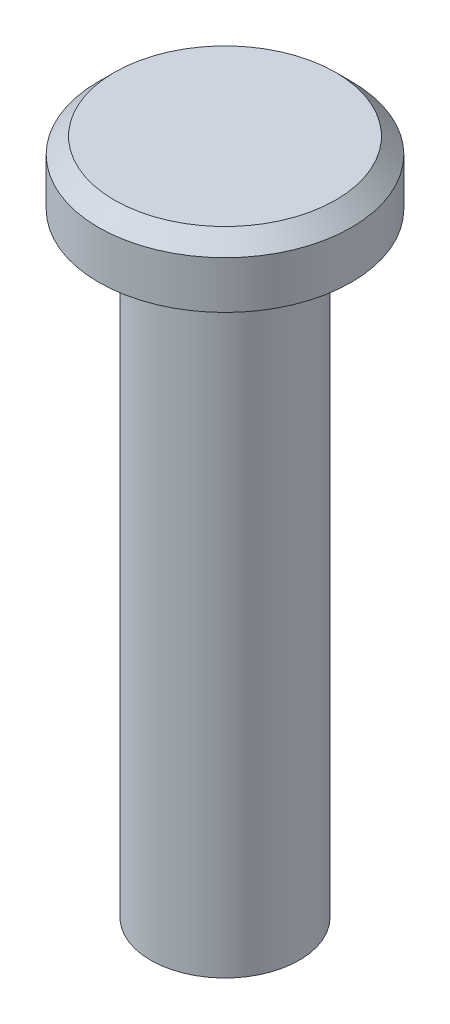
SolidWorks part; units mm, degrees
ref_plane "Front Plane" through (0, 0, 0) normal (0, 0, 1) x (1, 0, 0)
ref_plane "Top Plane" through (0, 0, 0) normal (0, 1, 0) x (1, 0, 0)
ref_plane "Right Plane" through (0, 0, 0) normal (1, 0, 0) x (0, 0, -1)
sketch "Sketch1" plane through (0, 0, 0) normal (0, 1, 0) x (1, 0, 0)
  circle A0 centre (0, 0) radius 2.35
  dimension "D1" = 4.7
extrude "Boss-Extrude1" add sketch "Sketch1" along normal blind 19.4
sketch "Sketch2" plane through (0, 19.4, 0) normal (0, 1, 0) x (1, 0, 0)
  circle A0 centre (0, 0) radius 4
  dimension "D1" = 8
extrude "Boss-Extrude2" add sketch "Sketch2" along normal blind 2
chamfer "Chamfer1" distance 0.5 angle 45 1 edges at (0, 21.4, 4)
sketch "Sketch3" plane through (0, 0, 0) normal (0, -1, 0) x (1, 0, 0)
  circle A0 centre (0, 0) radius 1.5
  dimension "D1" = 3
extrude "Cut-Extrude1" cut sketch "Sketch3" against normal blind 4
